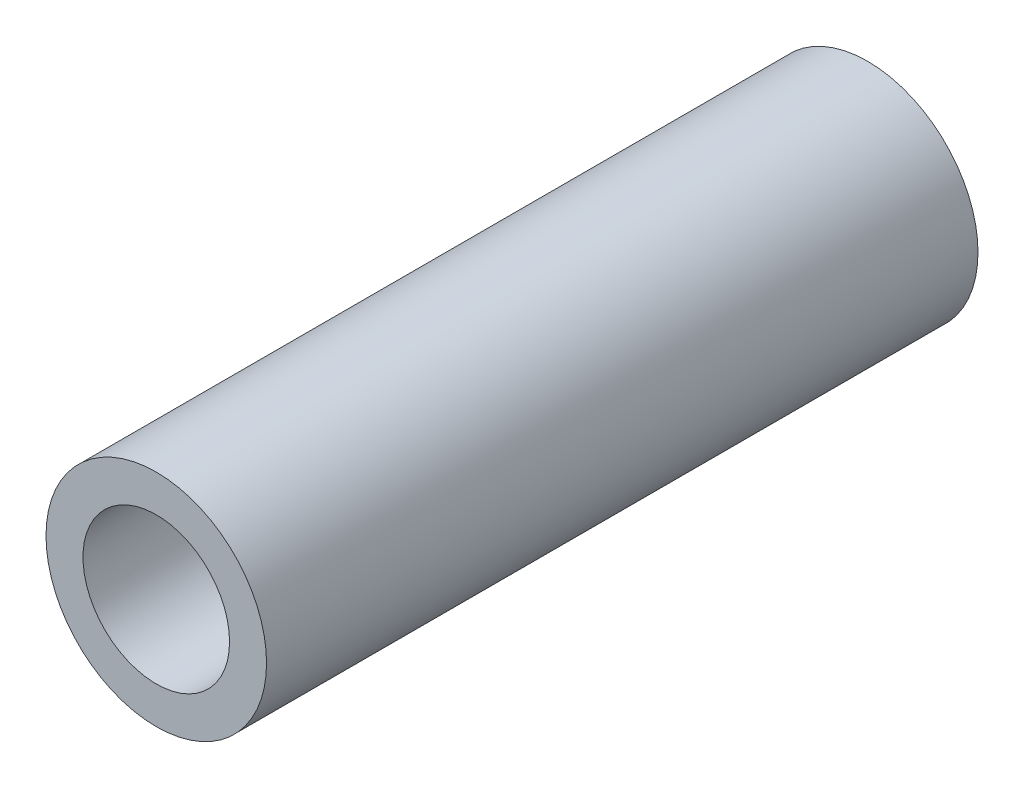
SolidWorks part; units mm, degrees
ref_plane "Front Plane" through (0, 0, 0) normal (1, 0, 0) x (0, 1, 0)
ref_plane "Top Plane" through (0, 0, 0) normal (0, 0, 1) x (0, 1, 0)
ref_plane "Right Plane" through (0, 0, 0) normal (0, 1, 0) x (-1, 0, 0)
sketch "Sketch1" plane through (0, 0, 0) normal (0, 0, 1) x (0, 1, 0)
  circle A0 centre (0, 0) radius 2.06
  circle A1 centre (0, 0) radius 3.1
  dimension "D1" = 4.12
  dimension "D2" = 6.2
extrude "Boss-Extrude1" add sketch "Sketch1" along normal blind 20
